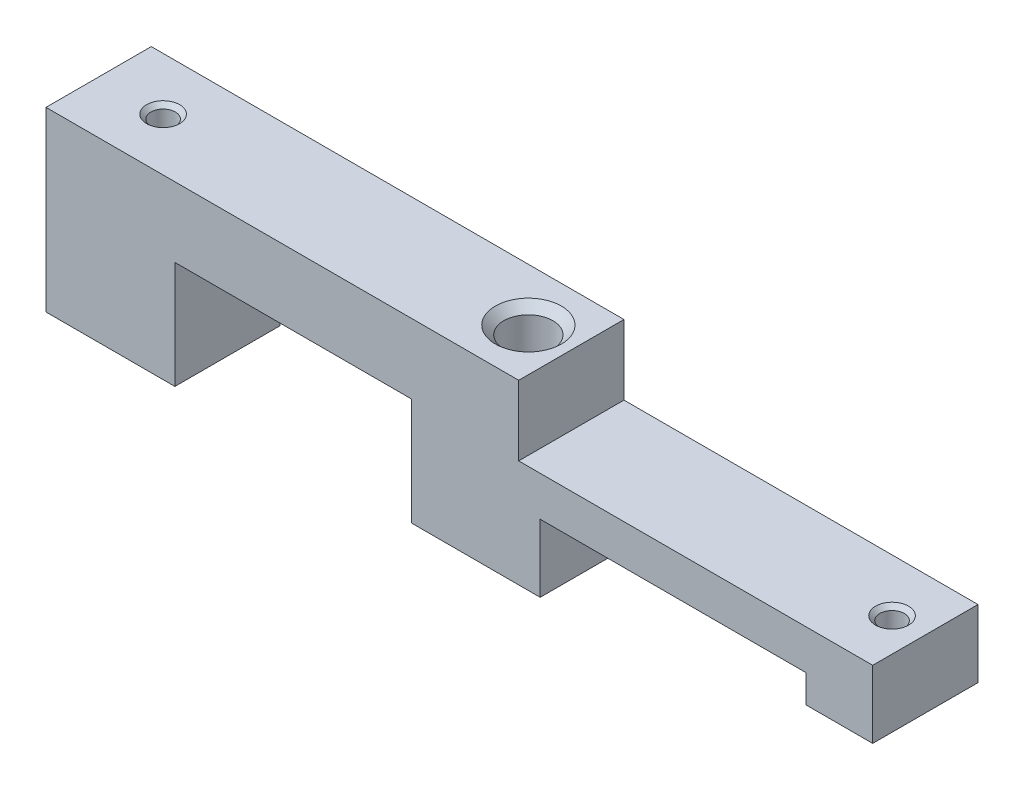
SolidWorks part; units mm, degrees
material "ABS"
ref_plane "Front Plane" through (0, 0, 0) normal (0, 0, 1) x (1, 0, 0)
ref_plane "Top Plane" through (0, 0, 0) normal (0, 1, 0) x (1, 0, 0)
ref_plane "Right Plane" through (0, 0, 0) normal (1, 0, 0) x (0, 0, -1)
sketch "Sketch1" plane through (0, 0, 0) normal (0, 0, 1) x (1, 0, 0)
  line L44 (0, 8.001) -> (-41.8502, 8.001)
  line L46 (-57.0902, 16.256) -> (-82.4902, 16.256)
  line L48 (-97.7302, 8.001) -> (-97.7302, -4.699)
  line L49 (-97.7302, -4.699) -> (-82.4902, -4.699)
  line L50 (-82.4902, -4.699) -> (-82.4902, 8.001)
  line L51 (-82.4902, 8.001) -> (-54.5502, 8.001)
  line L52 (-54.5502, 8.001) -> (-54.5502, -4.699)
  line L53 (-54.5502, -4.699) -> (-39.3102, -4.699)
  line L60 (-39.3102, -4.699) -> (-39.3102, 3.302)
  line L61 (-39.3102, 3.302) -> (-7.874, 3.302)
  line L62 (-7.874, 3.302) -> (-7.874, 0)
  line L63 (-7.874, 0) -> (0, 0)
  line L64 (0, 0) -> (0, 8.001)
  line L66 (-41.8502, 8.001) -> (-41.8502, 16.256)
  line L67 (-41.8502, 16.256) -> (-57.0902, 16.256)
  line L68 (-97.7302, 8.001) -> (-97.7302, 16.256)
  line L69 (-97.7302, 16.256) -> (-82.4902, 16.256)
  point P1 (0, 0)
  point P16 (-7.874, 0)
  point P19 (0, 0)
  point P20 (-32.6009, 4.2719)
  point P21 (0, 0)
  dimension "D1" = 12.7
  dimension "D2" = 27.94
  dimension "D5" = 8.001
  dimension "D6" = 31.4362
  dimension "D3" = 7.874
  dimension "D7" = 15.24
  dimension "D4" = 8.255
  dimension "D8" = 25.4
  dimension "D9" = 15.24
  dimension "D10" = 3.302
extrude "Boss-Extrude1" add sketch "Sketch1" along normal blind 12.446
sketch "Sketch2" plane through (0, 0, 0) normal (0, -1, 0) x (1, 0, 0)
  line L0 (-97.7302, 6.223) -> (0, 6.223) construction
  line L1 (-97.7302, 12.446) -> (-97.7302, 0) construction
  line L2 (0, 12.446) -> (0, 0) construction
  line L3 (-90.1102, 12.446) -> (-90.1102, 0) construction
  line L4 (-97.7302, 12.446) -> (-82.4902, 12.446) construction
  line L5 (-97.7302, 0) -> (-82.4902, 0) construction
  line L6 (-46.9302, 12.446) -> (-46.9302, 0) construction
  line L7 (-54.5502, 12.446) -> (-39.3102, 12.446) construction
  line L8 (-54.5502, 0) -> (-39.3102, 0) construction
  line L9 (-3.937, 12.446) -> (-3.937, 0) construction
  line L10 (-7.874, 12.446) -> (0, 12.446) construction
  line L11 (-7.874, 0) -> (0, 0) construction
  circle A0 centre (-90.1102, 6.223) radius 1.45
  circle A1 centre (-46.9302, 6.223) radius 2.9
  circle A2 centre (-3.937, 6.223) radius 1.45
  point P30 (0, 0)
  point P31 (0, 0)
  point P32 (0, 0)
  point P33 (0, 0)
  point P34 (0, 0)
  point P35 (0, 0)
  point P36 (0, 0)
  point P37 (0, 0)
  dimension "D1" = 2.9
  dimension "D2" = 5.8
  dimension "D3" = 2.9
extrude "Cut-Extrude1" cut sketch "Sketch2" against normal through all
chamfer "Chamfer2" distance 0.5 angle 45 2 edges at (-90.1102, 16.256, 4.773) (-2.487, 8.001, 6.223)
chamfer "Chamfer3" distance 1 angle 45 1 edges at (-46.9302, 16.256, 3.323)
equation "\"Spacing\"= 1.253in"
equation "\"D6@Sketch1\"=\"Spacing\"-\"someline\"+(\"midgap\")"
equation "\"HoleD\"= 4.70mm"
equation "\"M3D\" = 2.9mm"
equation "\"M6D\" = 5.8mm"
equation "\"D2@Sketch2\"=\"M6D\""
equation "\"D1@Sketch2\"=\"M3D\""
equation "\"D3@Sketch2\"=\"M3D\""
equation "\"someline\"= 0.6in"
equation "\"D7@Sketch1\"=\"someline\""
equation "\"D9@Sketch1\"=\"someline\""
equation "\"midgap\"= 0.58464567in"
equation "\"D3@Sketch1\"=\"mountheight\""
equation "\"mountheight\"= 0.310000in"
